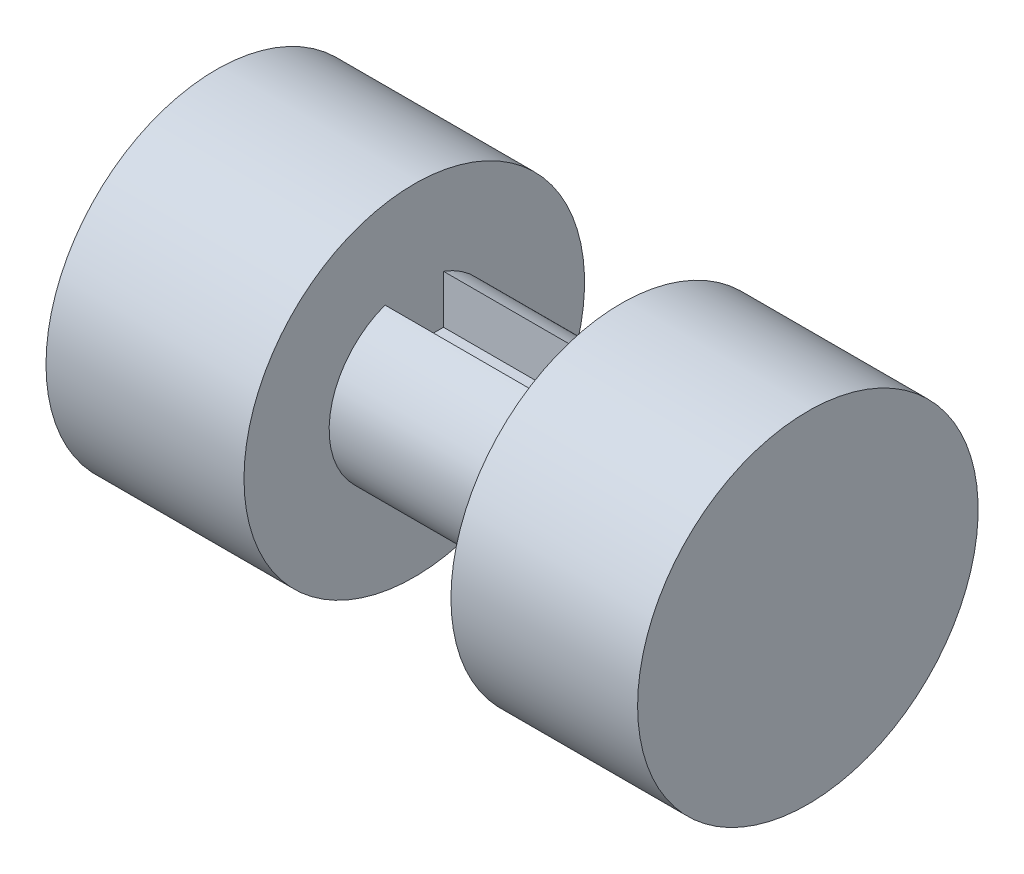
SolidWorks part; units mm, degrees
ref_plane "Plan de face" through (0, 0, 0) normal (0, 0, 1) x (1, 0, 0)
ref_plane "Plan de dessus" through (0, 0, 0) normal (0, 1, 0) x (1, 0, 0)
ref_plane "Plan de droite" through (0, 0, 0) normal (1, 0, 0) x (0, 0, -1)
sketch "Esquisse1" plane through (0, 0, 0) normal (0, 0, 1) x (1, 0, 0)
  line L0 (-44.0036, 0) -> (87.4771, 0)
  line L1 (87.4771, 0) -> (87.4771, 37.8431)
  line L2 (87.4771, 37.8431) -> (45.9951, 37.8431)
  line L3 (45.9951, 37.8431) -> (45.9951, 18.9216)
  line L4 (45.9951, 18.9216) -> (0, 18.9216)
  line L5 (0, 18.9216) -> (0, 37.8431)
  line L6 (0, 37.8431) -> (-44.0036, 37.8431)
  line L7 (-44.0036, 37.8431) -> (-44.0036, 0)
revolve "Révolution1" add sketch "Esquisse1" angle 360 about L0
sketch "Esquisse2" plane through (0, 0, 0) normal (0, 1, 0) x (1, 0, 0)
  line L0 (-61.8219, 0) -> (129.2896, 0) construction
  line L1 (0, -18.9216) -> (0, 18.9216) construction
  line L2 (0, 6.5) -> (45.9951, 6.5)
  line L3 (0, 6.5) -> (0, -6.5)
  line L4 (0, -6.5) -> (45.9951, -6.5)
  line L5 (45.9951, 6.5) -> (45.9951, -6.5)
  line L6 (0, 6.5) -> (45.9951, -6.5) construction
  line L7 (0, -6.5) -> (45.9951, 6.5) construction
  line L8 (45.9951, 37.8431) -> (45.9951, -37.8431) construction
  point P3 (22.9976, 0)
  dimension "D1" = 13
extrude "Enlèv. mat.-Extru.1" cut sketch "Esquisse2" against normal blind 13 from offset 20
